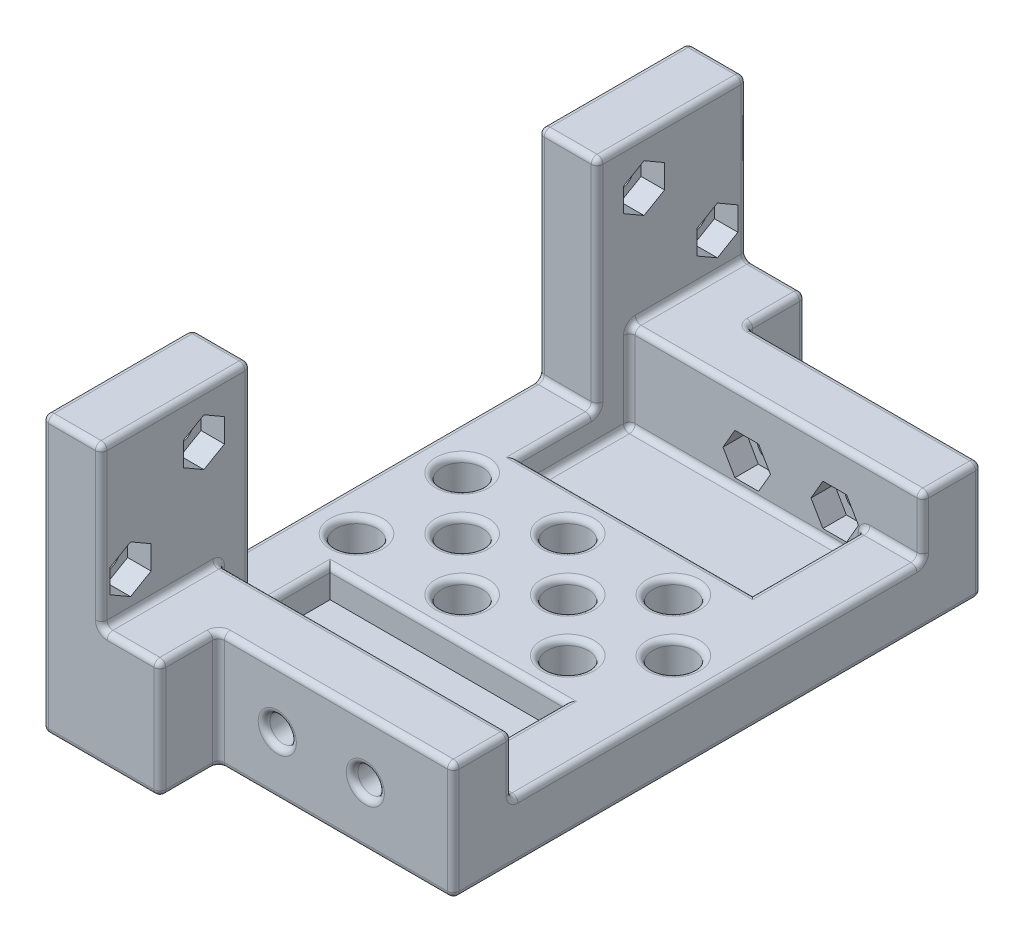
SolidWorks part; units mm, degrees
ref_plane "Front Plane" through (0, 0, 0) normal (0, 0, 1) x (1, 0, 0)
ref_plane "Top Plane" through (0, 0, 0) normal (0, 1, 0) x (1, 0, 0)
ref_plane "Right Plane" through (0, 0, 0) normal (1, 0, 0) x (0, 0, -1)
sketch "Sketch1" plane through (0, 0, 0) normal (1, 0, 0) x (0, 0, -1)
  line L1 (-38.6935, 11.3449) -> (-13.1935, 11.3449)
  line L2 (-38.6935, 11.3449) -> (-38.6935, -35.6551)
  line L3 (-38.6935, -35.6551) -> (71.3065, -35.6551)
  line L4 (71.3065, 11.3449) -> (71.3065, -35.6551)
  line L7 (45.8065, 11.3449) -> (71.3065, 11.3449)
  line L8 (-13.1935, 11.3449) -> (-13.1935, -25.6551)
  line L10 (-13.1935, -25.6551) -> (45.8065, -25.6551)
  line L12 (45.8065, -25.6551) -> (45.8065, 11.3449)
  circle A0 centre (-33.6935, -9.1551) radius 2.25
  circle A1 centre (-21.1935, 3.3449) radius 2.25
  circle A2 centre (66.3065, -9.1551) radius 2.25
  circle A3 centre (53.8065, 3.3449) radius 2.25
  dimension "D3" = 8
  dimension "D4" = 4.5
  dimension "D5" = 5
  dimension "D6" = 5
  dimension "D2" = 39
  dimension "D7" = 100
  dimension "D8" = 75
  dimension "D9" = 8
  dimension "D10" = 12.5
  dimension "D11" = 8
  dimension "D12" = 10
  dimension "D14" = 12.5
extrude "Boss-Extrude1" add sketch "Sketch1" along normal blind 10
sketch "Sketch2" plane through (10, 0, 0) normal (1, 0, 0) x (0, 0, -1)
  line L1 (-28.6935, -35.6551) -> (61.3065, -35.6551)
  line L5 (-38.6935, -35.6551) -> (71.3065, -35.6551) construction
  line L7 (-18.6935, -30.6551) -> (51.3065, -30.6551)
  line L10 (-28.6935, -15.6551) -> (-18.6935, -15.6551)
  line L11 (-18.6935, -30.6551) -> (-18.6935, -15.6551)
  line L14 (61.3065, -15.6551) -> (51.3065, -15.6551)
  line L15 (51.3065, -30.6551) -> (51.3065, -15.6551)
  line L16 (-28.6935, -15.6551) -> (-28.6935, -35.6551)
  line L17 (61.3065, -35.6551) -> (61.3065, -15.6551)
  line L18 (-28.6935, -35.6551) -> (-38.6935, -35.6551) construction
  line L19 (61.3065, -35.6551) -> (71.3065, -35.6551) construction
  dimension "D1" = 5
  dimension "D2" = 90
  dimension "D3" = 10
  dimension "D5" = 15
extrude "Boss-Extrude2" add sketch "Sketch2" along normal blind 50
sketch "Sketch8" plane through (10, 0, 0) normal (1, 0, 0) x (0, 0, -1)
  line L0 (-38.6935, -35.6551) -> (-28.6935, -35.6551) construction
  line L1 (-28.6935, -15.6551) -> (-38.6935, -15.6551)
  line L2 (-28.6935, -15.6551) -> (-28.6935, -35.6551)
  line L3 (-28.6935, -35.6551) -> (-38.6935, -35.6551)
  line L4 (-38.6935, -15.6551) -> (-38.6935, -35.6551)
  line L5 (61.3065, -35.6551) -> (71.3065, -35.6551) construction
  line L6 (61.3065, -15.6551) -> (71.3065, -15.6551)
  line L7 (61.3065, -15.6551) -> (61.3065, -35.6551)
  line L8 (61.3065, -35.6551) -> (71.3065, -35.6551)
  line L9 (71.3065, -15.6551) -> (71.3065, -35.6551)
  dimension "D1" = 10
extrude "Boss-Extrude3" add sketch "Sketch8" along normal blind 10
sketch "Sketch9" plane through (0, 0, 28.6935) normal (0, 0, 1) x (1, 0, 0)
  line L0 (20, -35.6551) -> (20, -15.6551) construction
  line L6 (60, -15.6551) -> (20, -15.6551) construction
  circle A0 centre (30, -25.6551) radius 2.25
  circle A1 centre (45, -25.6551) radius 2.25
  dimension "D3" = 4.5
  dimension "D1" = 10
  dimension "D2" = 10
  dimension "D4" = 15
extrude "Cut-Extrude4" cut sketch "Sketch9" against normal blind 110
sketch "Sketch10" plane through (10, 0, 0) normal (1, 0, 0) x (0, 0, -1)
  line L1 (-33.6935, -5.1136) -> (-37.1935, -7.1343)
  line L2 (-37.1935, -7.1343) -> (-37.1935, -11.1758)
  line L3 (-37.1935, -11.1758) -> (-33.6935, -13.1965)
  line L4 (-33.6935, -13.1965) -> (-30.1935, -11.1758)
  line L5 (-30.1935, -11.1758) -> (-30.1935, -7.1343)
  line L6 (-30.1935, -7.1343) -> (-33.6935, -5.1136)
  line L7 (-21.1935, 7.3864) -> (-24.6935, 5.3657)
  line L8 (-24.6935, 5.3657) -> (-24.6935, 1.3242)
  line L9 (-24.6935, 1.3242) -> (-21.1935, -0.6965)
  line L10 (-21.1935, -0.6965) -> (-17.6935, 1.3242)
  line L11 (-17.6935, 1.3242) -> (-17.6935, 5.3657)
  line L12 (-17.6935, 5.3657) -> (-21.1935, 7.3864)
  line L13 (53.8065, 7.3864) -> (50.3065, 5.3657)
  line L14 (50.3065, 5.3657) -> (50.3065, 1.3242)
  line L15 (50.3065, 1.3242) -> (53.8065, -0.6965)
  line L16 (53.8065, -0.6965) -> (57.3065, 1.3242)
  line L17 (57.3065, 1.3242) -> (57.3065, 5.3657)
  line L18 (57.3065, 5.3657) -> (53.8065, 7.3864)
  line L19 (66.3065, -5.1136) -> (62.8065, -7.1343)
  line L20 (62.8065, -7.1343) -> (62.8065, -11.1758)
  line L21 (62.8065, -11.1758) -> (66.3065, -13.1965)
  line L22 (66.3065, -13.1965) -> (69.8065, -11.1758)
  line L23 (69.8065, -11.1758) -> (69.8065, -7.1343)
  line L24 (69.8065, -7.1343) -> (66.3065, -5.1136)
  circle A0 centre (-33.6935, -9.1551) radius 3.5 construction
  circle A1 centre (-21.1935, 3.3449) radius 3.5 construction
  circle A2 centre (53.8065, 3.3449) radius 3.5 construction
  circle A3 centre (66.3065, -9.1551) radius 3.5 construction
  dimension "D1" = 7
extrude "Cut-Extrude5" cut sketch "Sketch10" against normal blind 4
sketch "Sketch11" plane through (0, 0, -51.3065) normal (0, 0, 1) x (1, 0, 0)
  line L1 (49.0415, -25.6551) -> (47.0207, -22.1551)
  line L2 (47.0207, -22.1551) -> (42.9793, -22.1551)
  line L3 (42.9793, -22.1551) -> (40.9585, -25.6551)
  line L4 (40.9585, -25.6551) -> (42.9793, -29.1551)
  line L5 (42.9793, -29.1551) -> (47.0207, -29.1551)
  line L6 (47.0207, -29.1551) -> (49.0415, -25.6551)
  line L7 (34.0415, -25.6551) -> (32.0207, -22.1551)
  line L8 (32.0207, -22.1551) -> (27.9793, -22.1551)
  line L9 (27.9793, -22.1551) -> (25.9585, -25.6551)
  line L10 (25.9585, -25.6551) -> (27.9793, -29.1551)
  line L11 (27.9793, -29.1551) -> (32.0207, -29.1551)
  line L12 (32.0207, -29.1551) -> (34.0415, -25.6551)
  circle A0 centre (45, -25.6551) radius 3.5 construction
  circle A1 centre (30, -25.6551) radius 3.5 construction
  dimension "D1" = 7
extrude "Cut-Extrude6" cut sketch "Sketch11" against normal blind 4
sketch "Sketch12" plane through (0, 0, 18.6935) normal (0, 0, -1) x (-1, 0, 0)
  line L1 (-40.9585, -25.6551) -> (-42.9793, -22.1551)
  line L2 (-42.9793, -22.1551) -> (-47.0207, -22.1551)
  line L3 (-47.0207, -22.1551) -> (-49.0415, -25.6551)
  line L4 (-49.0415, -25.6551) -> (-47.0207, -29.1551)
  line L5 (-47.0207, -29.1551) -> (-42.9793, -29.1551)
  line L6 (-42.9793, -29.1551) -> (-40.9585, -25.6551)
  line L7 (-25.9585, -25.6551) -> (-27.9793, -22.1551)
  line L8 (-27.9793, -22.1551) -> (-32.0207, -22.1551)
  line L9 (-32.0207, -22.1551) -> (-34.0415, -25.6551)
  line L10 (-34.0415, -25.6551) -> (-32.0207, -29.1551)
  line L11 (-32.0207, -29.1551) -> (-27.9793, -29.1551)
  line L12 (-27.9793, -29.1551) -> (-25.9585, -25.6551)
  circle A0 centre (-45, -25.6551) radius 3.5 construction
  circle A1 centre (-30, -25.6551) radius 3.5 construction
  dimension "D1" = 7
extrude "Cut-Extrude7" cut sketch "Sketch12" against normal blind 4
sketch "Sketch13" plane through (0, -30.6551, 0) normal (0, 1, 0) x (1, 0, 0)
  line L0 (60, 51.3065) -> (50, 51.3065)
  line L1 (60, 51.3065) -> (10, 51.3065) construction
  line L2 (50, 51.3065) -> (50, 32.3065)
  line L3 (50, 32.3065) -> (10, 32.3065)
  line L4 (10, 51.3065) -> (10, -18.6935) construction
  line L5 (10, 32.3065) -> (10, 0.3065)
  line L6 (10, 0.3065) -> (50, 0.3065)
  line L7 (50, 0.3065) -> (50, -18.6935)
  line L8 (60, -18.6935) -> (10, -18.6935) construction
  line L9 (50, -18.6935) -> (60, -18.6935)
  line L10 (60, -18.6935) -> (60, 51.3065)
  dimension "D1" = 32
  dimension "D2" = 10
extrude "Boss-Extrude4" add sketch "Sketch13" along normal blind 5
sketch "Sketch14" plane through (0, -25.6551, 0) normal (0, 1, 0) x (1, 0, 0)
  line L0 (7.5, 25.3065) -> (25.5, 25.3065) construction
  line L1 (25.5, 25.3065) -> (43.5, 25.3065) construction
  line L2 (7.5, 7.3065) -> (25.5, 7.3065) construction
  line L3 (25.5, 7.3065) -> (43.5, 7.3065) construction
  line L4 (25.5, 25.3065) -> (25.5, 16.3065) construction
  line L5 (34.5, 16.3065) -> (25.5, 16.3065) construction
  line L6 (25.5, 16.3065) -> (16.5, 16.3065) construction
  line L7 (25.5, 25.3065) -> (25.5, 32.3065) construction
  line L9 (50, 32.3065) -> (10, 32.3065) construction
  line L11 (25.5, 16.3065) -> (25.5, 7.3065) construction
  line L12 (7.5, 25.3065) -> (7.5, 7.3065) construction
  line L13 (16.5, 16.3065) -> (34.5, 16.3065) construction
  line L14 (25.5, 7.3065) -> (25.5, 0.3065) construction
  line L15 (52.5, 16.3065) -> (34.5, 16.3065) construction
  line L16 (10, 0.3065) -> (50, 0.3065) construction
  line L17 (52.5, 16.3065) -> (60, 16.3065) construction
  line L18 (60, -18.6935) -> (60, 51.3065) construction
  line L19 (7.5, 25.3065) -> (0, 25.3065) construction
  line L20 (0, 45.8065) -> (0, -13.1935) construction
  circle A0 centre (7.5, 25.3065) radius 3.5
  circle A1 centre (7.5, 7.3065) radius 3.5
  circle A2 centre (43.5, 25.3065) radius 3.5
  circle A3 centre (43.5, 7.3065) radius 3.5
  circle A4 centre (25.5, 25.3065) radius 3.5
  circle A5 centre (25.5, 7.3065) radius 3.5
  circle A6 centre (16.5, 16.3065) radius 3.5
  circle A7 centre (34.5, 16.3065) radius 3.5
  circle A8 centre (52.5, 16.3065) radius 3.5
  dimension "D1" = 7
  dimension "D2" = 18
extrude "Cut-Extrude8" cut sketch "Sketch14" against normal blind 10
fillet "Fillet5" radius 1 88 edges at (32.25, -25.6551, 28.6935) (0, 11.3449, -58.5565) (47.25, -25.6551, -61.3065) (47.25, -25.6551, 28.6935) (0, -12.1551, -71.3065) (0, -35.6551, -16.3065) (0, -12.1551, 38.6935) (5, 11.3449, 38.6935) (5, 11.3449, 13.1935) (5, -25.6551, 13.1935) (5, -25.6551, -45.8065) (5, 11.3449, -45.8065) (5, 11.3449, -71.3065) (10, -35.6551, -71.3065) (10, -35.6551, 38.6935) (10, 11.3449, -58.5565) (10, -7.1551, -45.8065) (0, -9.1551, 31.4435) (10, -25.6551, -39.0565) (0, 3.3449, 18.9435) (60, -20.6551, 18.6935) (30, -30.6551, 18.6935) (30, -30.6551, -51.3065) (10, -25.6551, 6.4435) (50, -28.1551, -51.3065) (10, -7.1551, 13.1935) (50, -28.1551, 18.6935) (60, -25.6551, -16.3065) (55, -25.6551, -51.3065) (50, -25.6551, -41.8065) (30, -25.6551, -32.3065) (0, -9.1551, -68.5565) (30, -25.6551, -0.3065) (50, -25.6551, 9.1935) (55, -25.6551, 18.6935) (25.5, -35.6551, -21.8065) (25.5, -25.6551, -21.8065) (43.5, -35.6551, -3.8065) (43.5, -25.6551, -3.8065) (43.5, -35.6551, -21.8065) (43.5, -25.6551, -21.8065) (10, 11.3449, 25.9435) (0, 3.3449, -56.0565) (7.5, -35.6551, -3.8065) (7.5, -25.6551, -3.8065) (25.5, -35.6551, -3.8065) (25.5, -25.6551, -3.8065) (16.5, -35.6551, -12.8065) (16.5, -25.6551, -12.8065) (34.5, -35.6551, -12.8065) (34.5, -25.6551, -12.8065) (52.5, -35.6551, -12.8065) (52.5, -25.6551, -12.8065) (7.5, -35.6551, -21.8065) (7.5, -25.6551, -21.8065) (40, -15.6551, 28.6935) (40, -35.6551, 28.6935) (40, -35.6551, -61.3065) (10, -15.6551, -61.3065) (40, -15.6551, -61.3065) (10, -23.1551, -51.3065) (35, -15.6551, -51.3065) (10, -23.1551, 18.6935) (10, -15.6551, 28.6935) (35, -15.6551, 18.6935) (60, -25.6551, 28.6935) (60, -35.6551, -16.3065) (10, -2.1551, 38.6935) (60, -25.6551, -61.3065) (60, -15.6551, -56.3065) (60, -20.6551, -51.3065) (60, -15.6551, 23.6935) (15, -15.6551, 38.6935) (20, -25.6551, 28.6935) (20, -15.6551, 33.6935) (20, -25.6551, 38.6935) (20, -35.6551, 33.6935) (10, -2.1551, -71.3065) (15, -15.6551, -71.3065) (20, -25.6551, -61.3065) (20, -35.6551, -66.3065) (20, -25.6551, -71.3065) (20, -15.6551, -66.3065) (0, 11.3449, 25.9435) (0, -7.1551, 13.1935) (0, -25.6551, -16.3065) (0, -7.1551, -45.8065) (32.25, -25.6551, -61.3065)
